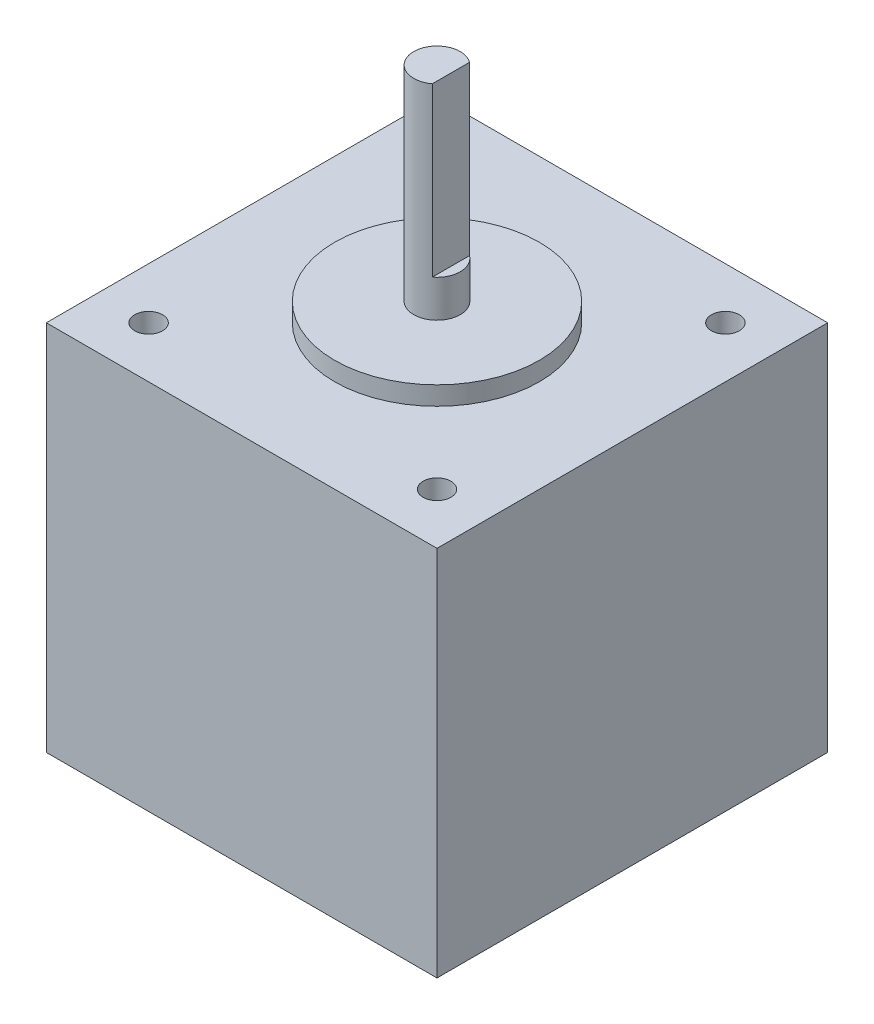
SolidWorks part; units mm, degrees
ref_plane "前视基准面" through (0, 0, 0) normal (0, 0, 1) x (1, 0, 0)
ref_plane "上视基准面" through (0, 0, 0) normal (0, 1, 0) x (1, 0, 0)
ref_plane "右视基准面" through (0, 0, 0) normal (1, 0, 0) x (0, 0, -1)
sketch "草图1" plane through (0, 0, 0) normal (0, 1, 0) x (1, 0, 0)
  line L0 (0, 0) -> (0, 42)
  line L1 (0, 42) -> (42, 42)
  line L2 (42, 42) -> (42, 0)
  line L3 (42, 0) -> (0, 0)
extrude "凸台-拉伸1" add sketch "草图1" along normal blind 40
sketch "草图2" plane through (0, 40, 0) normal (0, 1, 0) x (1, 0, 0)
  circle A0 centre (21, 21) radius 11
extrude "凸台-拉伸2" add sketch "草图2" along normal blind 2
sketch "草图3" plane through (0, 0, 0) normal (0, -1, 0) x (1, 0, 0)
  circle A0 centre (5.5, -36.5) radius 1.5
  circle A1 centre (36.5, -36.5) radius 1.5
  circle A2 centre (36.5, -5.5) radius 1.5
  circle A3 centre (5.5, -5.5) radius 1.5
extrude "切除-拉伸1" cut sketch "草图3" against normal blind 40
sketch "草图4" plane through (0, 42, 0) normal (0, 1, 0) x (1, 0, 0)
  circle A0 centre (21, 21) radius 2.5
extrude "凸台-拉伸3" add sketch "草图4" along normal blind 22
sketch "草图6" plane through (0, 64, 0) normal (0, 1, 0) x (1, 0, 0)
  line L0 (18.5, 21) -> (22.5, 21)
  line L1 (22.5, 19) -> (22.5, 23)
  circle A0 centre (21, 21) radius 2.5 construction
  circle A1 centre (21, 21) radius 2.5 construction
  circle A2 centre (21, 21) radius 2.5
  circle M3 centre (21, 21) radius 2.5
extrude "切除-拉伸2" cut sketch "草图6" against normal blind 18 contours L1 M3
